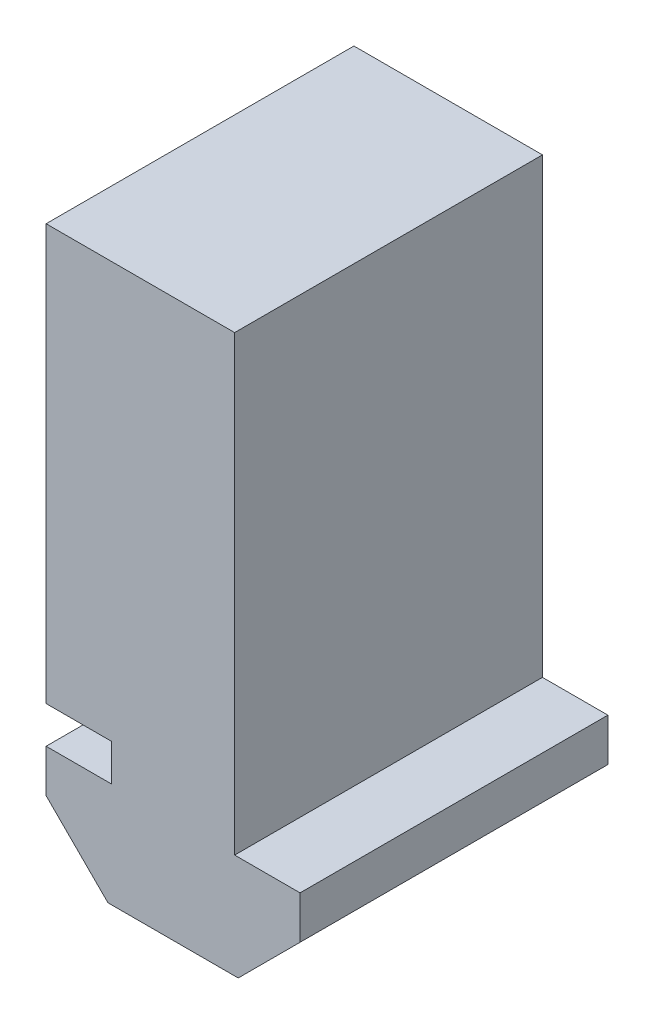
SolidWorks part; units mm, degrees
ref_plane "Piano frontale" through (0, 0, 0) normal (0, 0, 1) x (1, 0, 0)
ref_plane "Piano superiore" through (0, 0, 0) normal (0, 1, 0) x (1, 0, 0)
ref_plane "Piano destro" through (0, 0, 0) normal (1, 0, 0) x (0, 0, -1)
sketch "Schizzo2" plane through (0, 0, 0) normal (0, 0, 1) x (1, 0, 0)
  line L0 (0, 0) -> (0, 12.9875) construction
  line L1 (-4, 9.2) -> (-8.25, 9.2)
  line L2 (-8.25, 9.2) -> (-8.25, 36.2)
  line L3 (-8.25, 36.2) -> (4, 36.2)
  line L4 (4, 36.2) -> (4, 9.2)
  line L13 (-4.2322, 0) -> (4.2322, 0)
  line L14 (-8.25, 4.0178) -> (-4.2322, 0)
  line L15 (-8.25, 6.8) -> (-8.25, 4.0178)
  line L16 (-4, 6.8) -> (-8.25, 6.8)
  line L17 (-4, 9.2) -> (-4, 6.8)
  line L44 (8.25, 4.0178) -> (4.2322, 0)
  line L45 (8.25, 6.8) -> (8.25, 4.0178)
  line L46 (4, 6.8) -> (8.25, 6.8)
  line L72 (4, 9.2) -> (4, 6.8)
  dimension "D1" = 8.4645
  dimension "D2" = 4.0178
  dimension "D3" = 2.7822
  dimension "D4" = 8
  dimension "D5" = 2.4
  dimension "D6" = 16.5
  dimension "D7" = 27
extrude "Estrusione-Estrusione1" add sketch "Schizzo2" against normal blind 20
